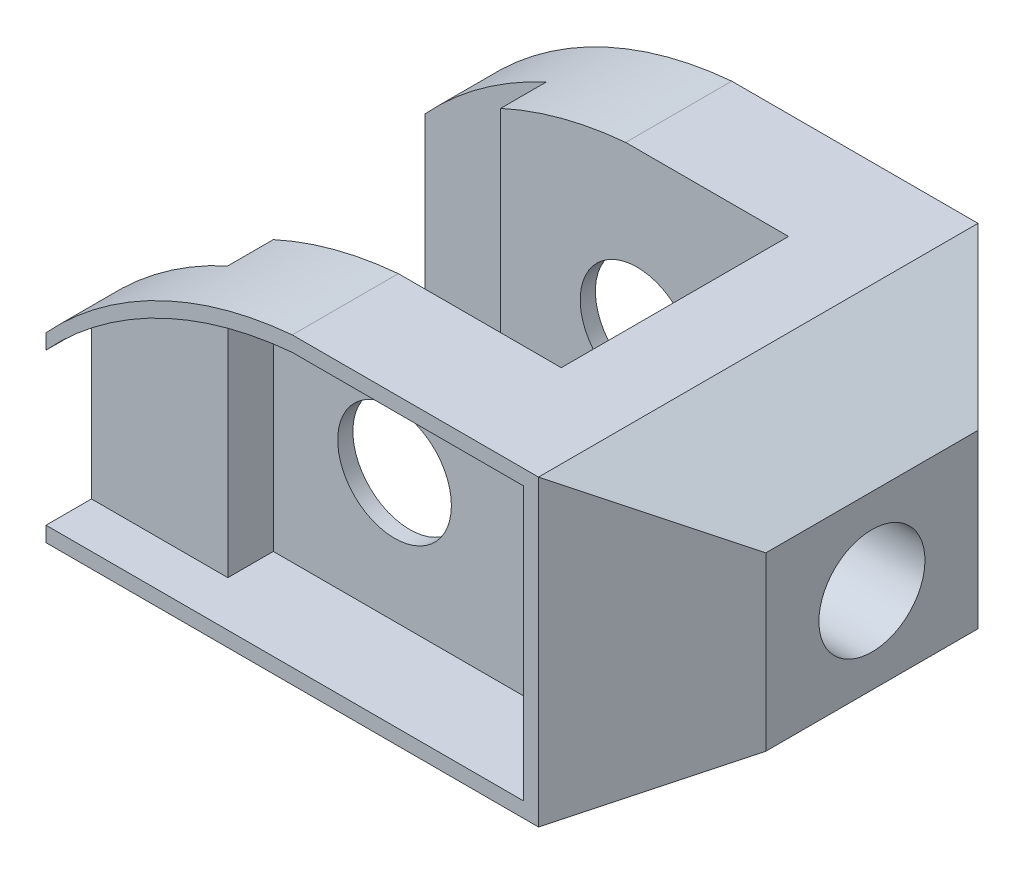
SolidWorks part; units mm, degrees
material "1060 Alloy"
ref_plane "Front Plane" through (0, 0, 0) normal (0, 0, 1) x (1, 0, 0)
ref_plane "Top Plane" through (0, 0, 0) normal (0, 1, 0) x (1, 0, 0)
ref_plane "Right Plane" through (0, 0, 0) normal (1, 0, 0) x (0, 0, -1)
sketch "Sketch1" plane through (0, 0, 0) normal (0, 0, 1) x (1, 0, 0)
  line L0 (0, 0) -> (-65, 0)
  line L2 (0, 0) -> (15, 8.6603)
  line L3 (15, 8.6603) -> (15, 31.3397)
  line L4 (15, 31.3397) -> (0, 40)
  line L5 (0, 40) -> (-32.5, 40)
  line L7 (-65, 0) -> (-65, 24)
  circle A0 centre (-31, 19) radius 7.5
  arc A1 (-65, 24) -> (-32.5, 40) centre (-28.1657, -9.8118) cw
  dimension "D8" = 15
  dimension "D11" = 50
  dimension "D1" = 65
  dimension "D2" = 31
  dimension "D3" = 30
  dimension "D4" = 15
  dimension "D5" = 30
  dimension "D6" = 15
  dimension "D7" = 40
  dimension "D9" = 19
  dimension "D10" = 24
extrude "Boss-Extrude1" add sketch "Sketch1" against normal blind 58
sketch "Sketch3" plane through (0, 40, 0) normal (0, 1, 0) x (1, 0, 0)
  line L0 (0.2927, 29) -> (-67.8122, 29) construction
  line L1 (-65, 50) -> (-49, 50)
  line L2 (0, 58) -> (15, 43)
  line L3 (15, 58) -> (15, 0) construction
  line L4 (15, 58) -> (0, 58) construction
  line L5 (-65, 58) -> (-65, 0) construction
  line L6 (-49, 50) -> (-49, 44)
  line L7 (-49, 44) -> (-11, 44)
  line L8 (-11, 44) -> (-11, 14)
  line L9 (0, 0) -> (15, 15)
  line L10 (-49, 8) -> (-49, 14)
  line L11 (-49, 14) -> (-11, 14)
  line L12 (-65, 8) -> (-49, 8)
  line L16 (15, 15) -> (15, 0)
  line L17 (15, 0) -> (0, 0)
  line L18 (15, 43) -> (15, 58)
  line L19 (15, 58) -> (0, 58)
  line L20 (-65, 50) -> (-65, 8)
  point P20 (-11, 29)
  dimension "D1" = 45
  dimension "D2" = 8
  dimension "D3" = 6
  dimension "D4" = 16
  dimension "D5" = 11
  dimension "D6" = 8
  dimension "D7" = 6
extrude "Cut-Extrude1" cut sketch "Sketch3" against normal blind 58
sketch "Sketch4" plane through (15, 0, 0) normal (1, 0, 0) x (0, 0, -1)
  circle A0 centre (29, 20) radius 7
  dimension "D3" = 14
  dimension "D1" = 29
  dimension "D2" = 20
extrude "Cut-Extrude2" cut sketch "Sketch4" against normal blind 58
sketch "Sketch5" plane through (0, 0, 0) normal (0, 0, 1) x (1, 0, 0)
  line L0 (-65, 2) -> (-2, 2)
  line L1 (-2, 2) -> (-2, 38)
  line L2 (-2, 38) -> (-32.5, 38)
  line L5 (0, 0) -> (0, 40) construction
  line L7 (0, 40) -> (-32.5, 40) construction
  line L9 (-65, 24) -> (-65, 0) construction
  arc A0 (-32.5, 38) -> (-65, 22) centre (-28.1657, -11.8118) ccw
  dimension "D4" = 2
  dimension "D1" = 2
  dimension "D2" = 2
extrude "Cut-Extrude3" cut sketch "Sketch5" against normal blind 6 and the other way through all
sketch "Sketch7" plane through (0, 0, -6) normal (0, 0, 1) x (1, 0, 0)
  line L0 (-47, 34.5053) -> (-47, 2)
  line L1 (-2, 2) -> (-65, 2) construction
  line L2 (-47, 2) -> (-2, 2)
  line L3 (-2, 2) -> (-2, 38)
  line L4 (-2, 38) -> (-32.5, 38)
  arc A0 (-32.5, 38) -> (-65, 22) centre (-28.1657, -11.8118) ccw construction
  arc A1 (-47, 34.5053) -> (-32.5, 38) centre (-28.1657, -11.8118) cw
  dimension "D1" = 18
extrude "Cut-Extrude5" cut sketch "Sketch7" against normal blind 6
sketch "Sketch8" plane through (0, 0, -58) normal (0, 0, -1) x (-1, 0, 0)
  line L0 (2, 2) -> (65, 2)
  line L1 (65, 24) -> (65, 0) construction
  line L2 (2, 2) -> (2, 38)
  line L3 (2, 38) -> (32.5, 38)
  line L4 (0, 0) -> (0, 40) construction
  line L5 (0, 40) -> (32.5, 40) construction
  line L6 (65, 22) -> (65, 2)
  arc A0 (32.5, 38) -> (65, 22) centre (28.1657, -11.8118) cw
  dimension "D4" = 50
  dimension "D1" = 2
  dimension "D2" = 2
  dimension "D3" = 2
  dimension "D5" = 2
extrude "Cut-Extrude6" cut sketch "Sketch8" against normal blind 6
sketch "Sketch9" plane through (0, 0, -52) normal (0, 0, -1) x (-1, 0, 0)
  line L0 (47, 34.5053) -> (47, 2)
  line L1 (2, 2) -> (65, 2) construction
  line L2 (47, 2) -> (2, 2)
  line L3 (2, 2) -> (2, 38)
  line L4 (2, 38) -> (32.5, 38)
  arc A0 (65, 22) -> (32.5, 38) centre (28.1657, -11.8118) ccw construction
  arc A1 (32.5, 38) -> (47, 34.5053) centre (28.1657, -11.8118) cw
  dimension "D1" = 18
extrude "Cut-Extrude7" cut sketch "Sketch9" against normal blind 6
